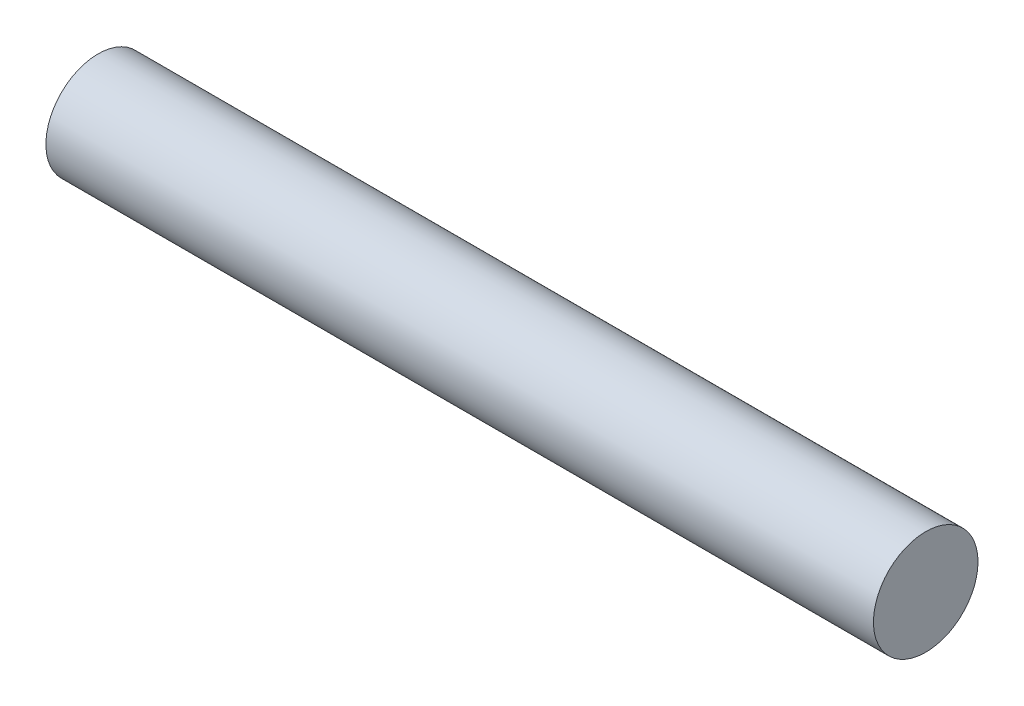
SolidWorks part; units mm, degrees
ref_plane "Front Plane" through (0, 0, 0) normal (0, 0, 1) x (1, 0, 0)
ref_plane "Top Plane" through (0, 0, 0) normal (0, 1, 0) x (1, 0, 0)
ref_plane "Right Plane" through (0, 0, 0) normal (1, 0, 0) x (0, 0, -1)
sketch "Sketch2" plane through (0, 0, 0) normal (1, 0, 0) x (0, 0, -1)
  circle A0 centre (0, 0) radius 1.2
  dimension "D1" = 2.4
extrude "Boss-Extrude1" add sketch "Sketch2" along normal blind 19
